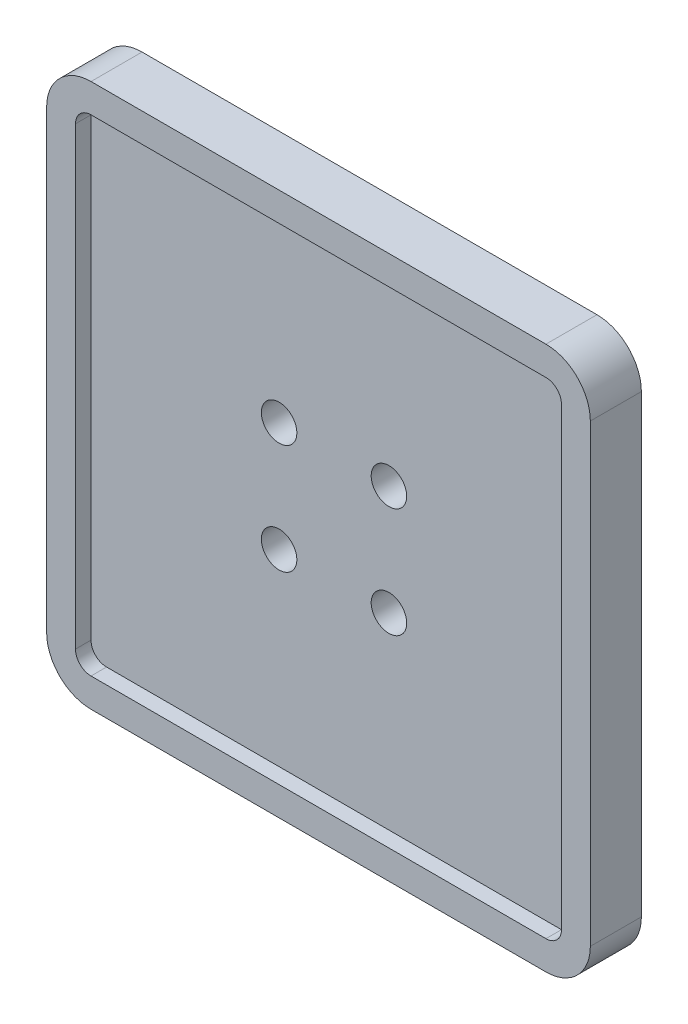
SolidWorks part; units mm, degrees
ref_plane "Front Plane" through (0, 0, 0) normal (0, 0, 1) x (1, 0, 0)
ref_plane "Top Plane" through (0, 0, 0) normal (0, 1, 0) x (1, 0, 0)
ref_plane "Right Plane" through (0, 0, 0) normal (1, 0, 0) x (0, 0, -1)
sketch "Sketch1" plane through (0, 0, 0) normal (0, 0, 1) x (1, 0, 0)
  line L1 (-4.9497, 4.9497) -> (4.9497, 4.9497) construction
  line L2 (-4.9497, 4.9497) -> (-4.9497, -4.9497) construction
  line L3 (-4.9497, -4.9497) -> (4.9497, -4.9497) construction
  line L4 (4.9497, 4.9497) -> (4.9497, -4.9497) construction
  line L5 (-4.9497, 4.9497) -> (4.9497, -4.9497) construction
  line L6 (-4.9497, -4.9497) -> (4.9497, 4.9497) construction
  line L14 (-24.5, -20.5) -> (-24.5, 20.5)
  line L15 (-20.5, 24.5) -> (20.5, 24.5)
  line L16 (24.5, 20.5) -> (24.5, -20.5)
  line L17 (20.5, -24.5) -> (-20.5, -24.5)
  line L18 (-24.5, 24.5) -> (24.5, -24.5) construction
  line L19 (-24.5, -24.5) -> (24.5, 24.5) construction
  circle A1 centre (-4.9497, 4.9497) radius 1.6
  circle A2 centre (4.9497, 4.9497) radius 1.6
  circle A3 centre (4.9497, -4.9497) radius 1.6
  circle A4 centre (-4.9497, -4.9497) radius 1.6
  arc A5 (24.5, -20.5) -> (20.5, -24.5) centre (20.5, -20.5) cw
  arc A6 (-24.5, -20.5) -> (-20.5, -24.5) centre (-20.5, -20.5) ccw
  arc A7 (20.5, 24.5) -> (24.5, 20.5) centre (20.5, 20.5) cw
  arc A8 (-24.5, 20.5) -> (-20.5, 24.5) centre (-20.5, 20.5) cw
  point P2 (0, 0)
  point P11 (0, 0)
  point P14 (0, 0)
  point P15 (-4.9497, 22)
  point P16 (-0.7737, 20.7751)
  point P17 (0, 24.6978)
  point P18 (-10.6264, 24.8637)
  point P19 (43.5067, 18.0326)
  point P20 (43.0176, 21.75)
  point P21 (0, 0)
  point P22 (-51.8728, -21.75)
  point P40 (0, 0)
  point P41 (0, 0)
  dimension "D1" = 4
  dimension "D3" = 3.2
  dimension "D4" = 49
  dimension "D2" = 14
extrude "Boss-Extrude1" add sketch "Sketch1" along normal blind 4.6
sketch "Sketch5" plane through (0, 0, 4.6) normal (0, 0, 1) x (1, 0, 0)
  line L8 (21.9, -20.5) -> (21.9, 20.5)
  line L9 (20.5, 21.9) -> (-20.5, 21.9)
  line L10 (-21.9, 20.5) -> (-21.9, -20.5)
  line L11 (-20.5, -21.9) -> (20.5, -21.9)
  line L12 (21.9, -20.5) -> (21.9, 20.5)
  line L13 (20.5, 21.9) -> (-20.5, 21.9)
  line L14 (-21.9, 20.5) -> (-21.9, -20.5)
  line L15 (-20.5, -21.9) -> (20.5, -21.9)
  arc A8 (20.5, -21.9) -> (21.9, -20.5) centre (20.5, -20.5) ccw
  arc A9 (21.9, 20.5) -> (20.5, 21.9) centre (20.5, 20.5) ccw
  arc A10 (-20.5, 21.9) -> (-21.9, 20.5) centre (-20.5, 20.5) ccw
  arc A11 (-21.9, -20.5) -> (-20.5, -21.9) centre (-20.5, -20.5) ccw
  arc A12 (20.5, -21.9) -> (21.9, -20.5) centre (20.5, -20.5) ccw
  arc A13 (21.9, 20.5) -> (20.5, 21.9) centre (20.5, 20.5) ccw
  arc A14 (-20.5, 21.9) -> (-21.9, 20.5) centre (-20.5, 20.5) ccw
  arc A15 (-21.9, -20.5) -> (-20.5, -21.9) centre (-20.5, -20.5) ccw
  dimension "D1" = 2.6
extrude "Cut-Extrude5" cut sketch "Sketch5" against normal blind 1.4
